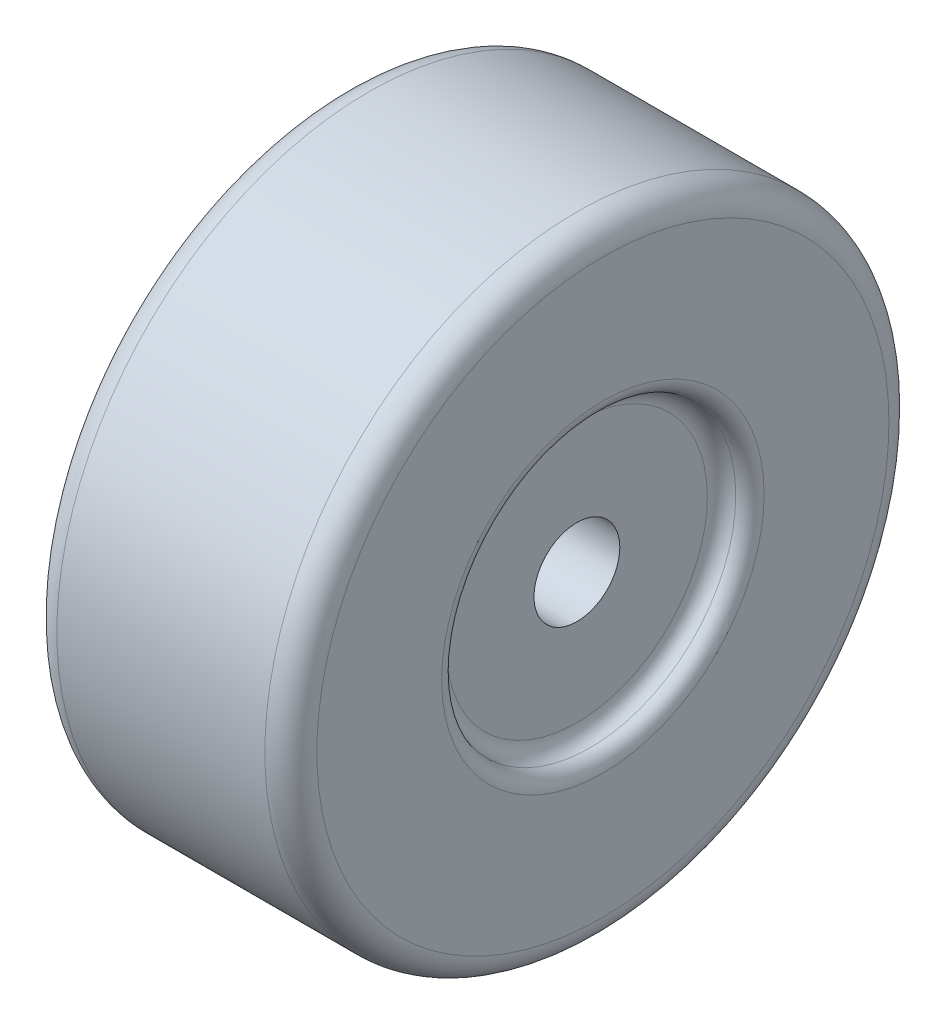
SolidWorks part; units mm, degrees
ref_plane "Front" through (0, 0, 0) normal (0, 0, 1) x (1, 0, 0)
ref_plane "Top" through (0, 0, 0) normal (0, 1, 0) x (1, 0, 0)
ref_plane "Right" through (0, 0, 0) normal (1, 0, 0) x (0, 0, -1)
sketch "草图1" plane through (0, 0, 0) normal (1, 0, 0) x (0, 0, -1)
  circle A0 centre (0, 0) radius 60
  dimension "D1" = 120
extrude "凸台-拉伸1" add sketch "草图1" along normal mid plane 50
fillet "圆角1" radius 5 2 edges at (-25, 0, -60) (25, 0, -60)
sketch "草图2" plane through (25, 0, 0) normal (1, 0, 0) x (0, 0, -1)
  circle A0 centre (0, 0) radius 8.25
  dimension "D1" = 16.5
extrude "切除-拉伸1" cut sketch "草图2" against normal through all
chamfer "倒角1" distance 3 angle 45 2 edges at (-25, 0, -8.25) (25, 0, -8.25)
sketch "草图3" plane through (25, 0, 0) normal (1, 0, 0) x (0, 0, -1)
  circle A0 centre (0, 0) radius 28
  dimension "D1" = 56
extrude "切除-拉伸2" cut sketch "草图3" against normal blind 5
fillet "圆角2" radius 3 1 edges at (25, 0, -28)
fillet "圆角3" radius 3 1 edges at (20, 0, -28)
sketch "草图4" plane through (-25, 0, 0) normal (-1, 0, 0) x (0, 0, 1)
  circle A0 centre (0, 0) radius 28
  dimension "D1" = 56
extrude "切除-拉伸3" cut sketch "草图4" against normal blind 5
fillet "圆角4" radius 3 1 edges at (-25, 0, 28)
fillet "圆角5" radius 3 1 edges at (-20, 0, 28)
